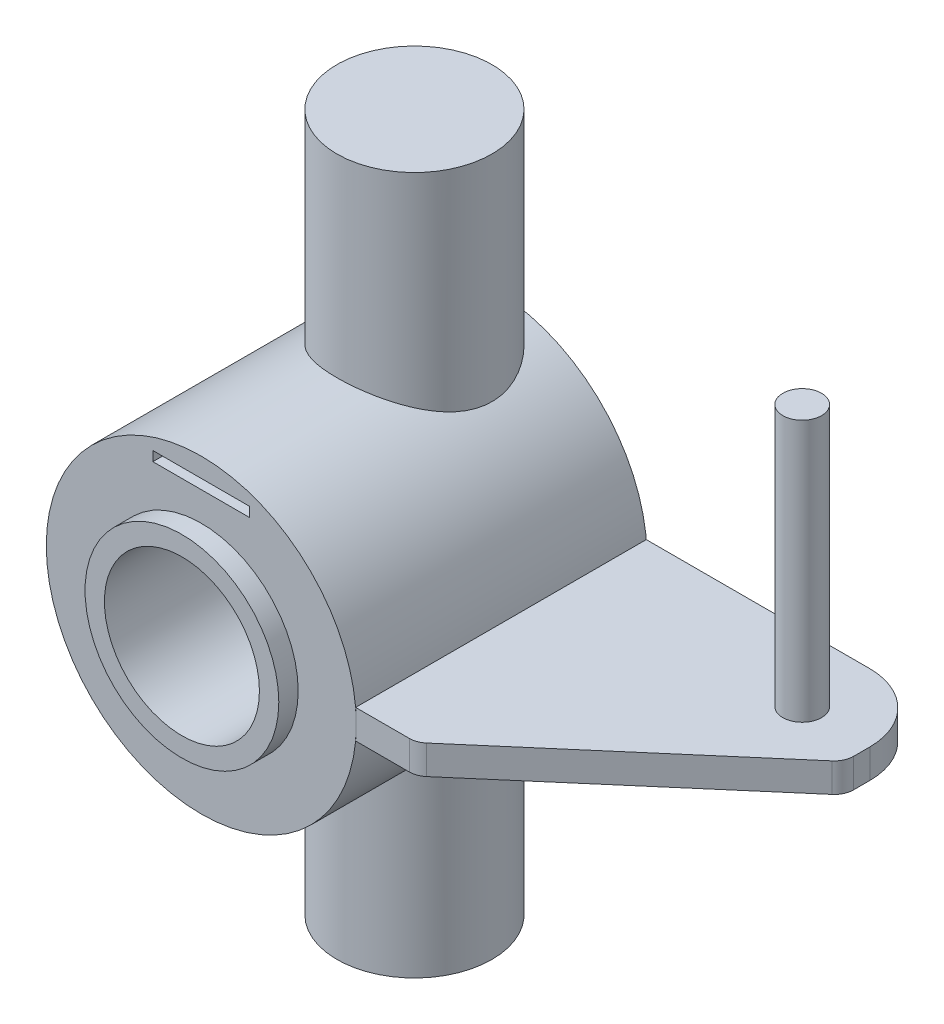
SolidWorks part; units mm, degrees
ref_plane "Front Plane" through (0, 0, 0) normal (0, 0, 1) x (1, 0, 0)
ref_plane "Top Plane" through (0, 0, 0) normal (0, 1, 0) x (1, 0, 0)
ref_plane "Right Plane" through (0, 0, 0) normal (1, 0, 0) x (0, 0, -1)
sketch "Sketch1" plane through (0, 0, 0) normal (0, 0, 1) x (1, 0, 0)
  line L0 (8.8, 8) -> (-8.8, 8) construction
  line L1 (8.8, 0) -> (-8.8, 0) construction
  circle A0 centre (0, 0) radius 8
  dimension "D1" = 16
extrude "Boss-Extrude1" add sketch "Sketch1" along normal blind 15
sketch "Sketch2" plane through (0, 0, 15) normal (0, 0, 1) x (1, 0, 0)
  circle A0 centre (0, 0) radius 5
  circle A1 centre (0, 0) radius 4
  dimension "D1" = 10
  dimension "D2" = 8
extrude "Boss-Extrude2" add sketch "Sketch2" along normal blind 1 contours A0
sketch "Sketch3" plane through (0, 0, 15) normal (0, 0, 1) x (1, 0, 0)
  circle A1 centre (0, 0) radius 4
  circle A2 centre (0, 0) radius 4
  dimension "D1" = 0
extrude "Cut-Extrude1" cut sketch "Sketch3" against normal blind 15
ref_plane "Plane1" through (0, 8, 0) normal (0, 1, 0) x (1, 0, 0)
sketch "Sketch4" plane through (0, 8, 0) normal (0, 1, 0) x (1, 0, 0)
  circle A5 centre (0, -4) radius 4
  dimension "D1" = 8
  dimension "D2" = 4
extrude "Boss-Extrude3" add sketch "Sketch4" along normal blind 10 and the other way up to surface separate body other way up to face at (8, 0, 15)
ref_plane "Plane2" through (0, -8, 0) normal (0, -1, 0) x (-1, 0, 0)
sketch "Sketch6" plane through (0, -8, 0) normal (0, -1, 0) x (-1, 0, 0)
  circle A0 centre (0, -4) radius 4
  dimension "D1" = 4
  dimension "D2" = 8
extrude "Boss-Extrude4" add sketch "Sketch6" along normal blind 10 and the other way up to surface other way up to face at (8, 0, 15)
ref_plane "Plane3" through (8, 0, 0) normal (1, 0, 0) x (0, 0, -1)
sketch "Sketch7" plane through (8, 0, 0) normal (1, 0, 0) x (0, 0, -1)
  line L9 (0, -0.75) -> (-15, -0.75)
  line L10 (0, -0.75) -> (0, 0.75)
  line L11 (0, 0.75) -> (-15, 0.75)
  line L12 (-15, -0.75) -> (-15, 0.75)
  point P4 (0, 0)
  dimension "D1" = 15
  dimension "D2" = 1.5
extrude "Boss-Extrude5" add sketch "Sketch7" along normal blind 15 and the other way up to surface separate body other way up to face at (8, 0, 15)
sketch "Sketch9" plane through (0, -0.75, 0) normal (0, -1, 0) x (1, 0, 0)
  line L4 (7.9648, 15) -> (7.9648, 0)
  line L5 (7.9648, 0) -> (23, 0)
  line L6 (23, 0) -> (23, 15)
  line L7 (23, 15) -> (7.9648, 15)
  line L9 (7.9648, 0) -> (23, 0)
  line L10 (23, 0) -> (23, 15)
  line L11 (23, 15) -> (7.9648, 15)
  line L12 (7.9648, 15) -> (7.9648, 0)
  circle A0 centre (19.5, 3.5) radius 3.5
  line M8 (23, 0) -> (23, 15)
  dimension "D1" = 0
  dimension "D2" = 7
extrude "Cut-Extrude2" cut sketch "Sketch9" against normal blind 15 contours A0 L9 M8
sketch "Sketch11" plane through (0, -0.75, 0) normal (0, -1, 0) x (-1, 0, 0)
  line L0 (-11.1081, -15) -> (-23, -4.7928) construction
  line L1 (-23, -15) -> (-7.9648, -15) construction
  line L2 (-23, -15) -> (-23, -3.5) construction
  line M3 (-23, -3.5) -> (-23, -15)
  line M4 (-23, -15) -> (-7.9648, -15)
extrude "Cut-Extrude3" cut sketch "Sketch11" against normal blind 15 contours L0 M4 M3
fillet "Fillet1" radius 1 1 edges at (11.1081, 0, 15)
fillet "Fillet2" radius 1 1 edges at (23, 0, 4.7928)
sketch "Sketch12" plane through (0, -0.75, 0) normal (0, -1, 0) x (1, 0, 0)
  arc A2 (19.5, 0) -> (23, 3.5) centre (19.5, 3.5) ccw construction
  arc A3 (19.5, 0) -> (23, 3.5) centre (19.5, 3.5) ccw
  circle A4 centre (19.4463, 3.435) radius 1
  point P1 (21.9749, 1.0251)
  dimension "D1" = 2
  dimension "D3" = 2.5286
  dimension "D2" = 3.435
sketch "Sketch13" plane through (0, 0, 0) normal (0, 1, 0) x (1, 0, 0)
  line L0 (0, 0) -> (0, -16.3088) construction
extrude "Boss-Extrude6" add sketch "Sketch12" against normal blind 15 contours A4
sketch "Sketch14" plane through (0, 0, 15) normal (0, 0, 1) x (1, 0, 0)
  line L0 (-2.5, 7) -> (2.5, 6.5) construction
  line L1 (-2.5, 7) -> (2.5, 7)
  line L2 (-2.5, 7) -> (-2.5, 6.5)
  line L3 (-2.5, 6.5) -> (2.5, 6.5)
  line L4 (2.5, 7) -> (2.5, 6.5)
  point P4 (0, 6.75)
  dimension "D1" = 5
  dimension "D2" = 0.5
  dimension "D3" = 7
extrude "Cut-Extrude4" cut sketch "Sketch14" against normal blind 1
